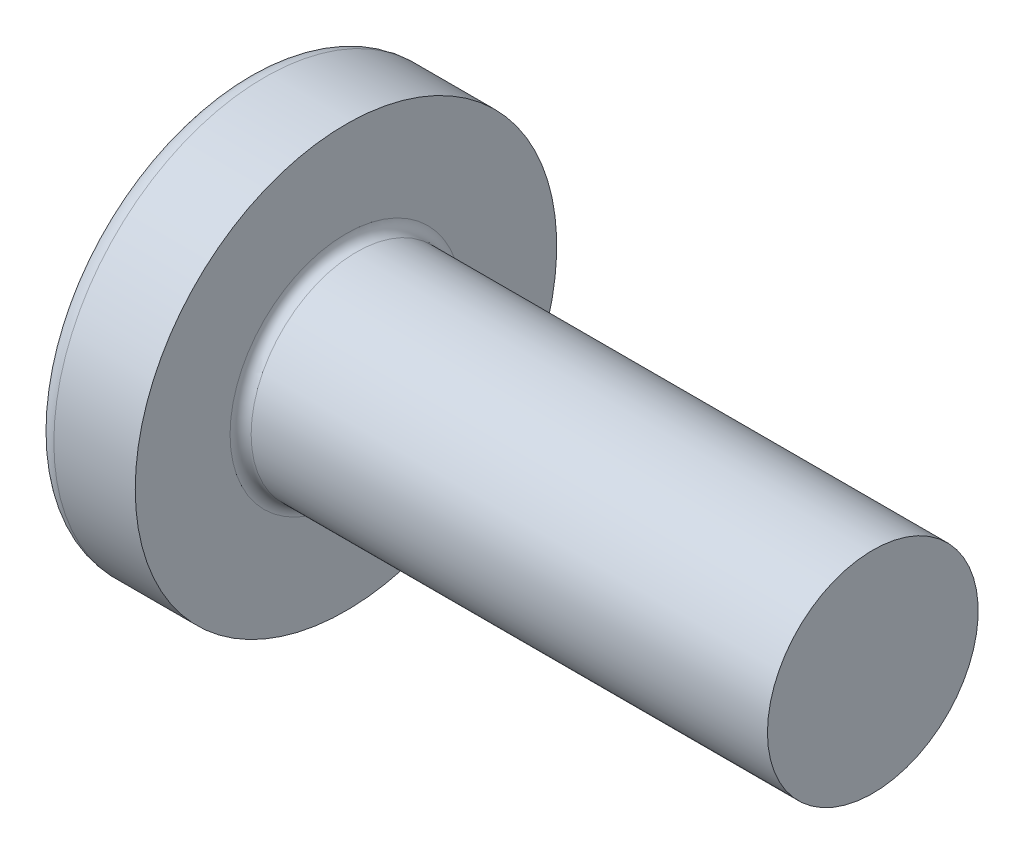
SolidWorks part; units mm, degrees
ref_plane "Plane1" through (0, 0, 0) normal (0, 0, 1) x (1, 0, 0)
ref_plane "Plane2" through (0, 0, 0) normal (0, 1, 0) x (1, 0, 0)
ref_plane "Plane3" through (0, 0, 0) normal (1, 0, 0) x (0, 0, -1)
sketch "BodySke" plane through (0, 0, 0) normal (0, 0, 1) x (1, 0, 0)
  line L0 (3.1, 2) -> (3.1, 4)
  line L1 (3.45, 6.35) -> (3.45, -3.175) construction
  line L2 (-25.4, 0) -> (127, 0) construction
  line L3 (13.1, 0) -> (0, 0)
  line L4 (3.1, 2) -> (13.1, 2)
  line L5 (13.1, 2) -> (13.1, 0)
  line L6 (1.5553, 4) -> (3.1, 4)
  line L8 (3.1, 6.35) -> (3.1, -3.175) construction
  arc A0 (1.2654, 3.8534) -> (0, 0) centre (6.5, 0) ccw
  arc A2 (1.2654, 3.8534) -> (1.5553, 4) centre (1.5553, 3.64) cw
  dimension "Head_fillet_rad" = 0.36
  dimension "Head_crown_rad" = 6.5
  dimension "Head_ht" = 3.1
  dimension "Diameter" = 4
  dimension "Length" = 10
  dimension "Head_dia" = 8
  dimension "Advance" = 0.7
  dimension "Thread_nom" = 10
revolve "Base-Revolve" add sketch "BodySke"
cosmetic thread "ThreadCosmetic" [suppressed]
fillet "Fillet1" radius 0.2
sketch "Sketch3" plane through (0, 0, 0) normal (1, 0, 0) x (0, 0, -1)
  line L0 (0.515, -2.15) -> (-0.515, -2.15)
  line L1 (0.515, -2.15) -> (0.515, 2.15)
  line L2 (-0.515, 2.15) -> (0.515, 2.15)
  line L3 (-0.515, 2.15) -> (-0.515, -2.15)
  dimension "D1" = 2.15
  dimension "Cross_dia" = 4.3
  dimension "D2" = 0.515
  dimension "Cross_width" = 1.03
ref_plane "Plane4" through (2.34, 0, 0) normal (1, 0, 0) x (0, 0, -1)
sketch "Sketch4" plane through (2.34, 0, 0) normal (1, 0, 0) x (0, 0, -1)
  line L0 (0.515, -0.9833) -> (-0.515, -0.9833)
  line L1 (0.515, -0.9833) -> (0.515, 0.9833)
  line L2 (-0.515, 0.9833) -> (0.515, 0.9833)
  line L3 (-0.515, 0.9833) -> (-0.515, -0.9833)
  dimension "D1" = 1.03
  dimension "D2" = 1.9666
  dimension "D3" = 0.515
  dimension "D4" = 0.9833
loft "Recess" cut profiles "Sketch3", "Sketch4"
pattern_circular "RecPat" count 2 every 90
sketch "RecCorSke" plane through (0, 0, 0) normal (0, 0, 1) x (1, 0, 0)
  line L0 (-3.175, 0) -> (15.875, 0) construction
  line L1 (-25.4, 0) -> (127, 0) construction
  line L2 (0, 0) -> (0, 1.0146)
  line L3 (0, 1.0146) -> (2.34, 0.851)
  line L4 (2.34, 0.851) -> (2.6165, 0)
  line L5 (2.6165, 0) -> (0, 0)
  dimension "Diameter" = 1.702
  dimension "Depth" = 2.34
  dimension "Draft_angle" = 4
  dimension "Bottom_angle" = 18
revolve "RecessCore" cut sketch "RecCorSke" angle 360 about L0
sketch "ThdSchSke" plane through (0, 0, 0) normal (0, 0, 1) x (1, 0, 0)
  line L0 (4.5, -1.61) -> (4.2269, -2)
  line L1 (4.5, -1.61) -> (4.7731, -2)
  line L2 (4.7731, -2) -> (4.7731, -2.5)
  line L3 (-3.175, 0) -> (5.1513, 0) construction
  line L5 (4.7731, -2.5) -> (4.2269, -2.5)
  line L6 (4.2269, -2.5) -> (4.2269, -2)
  dimension "Thread_minor" = 3.22
  dimension "Diameter" = 4
  dimension "Start" = 4.5
  dimension "SideAngle" = 55
  dimension "VeeAngle" = 70
  dimension "Overcut" = 5
revolve "ThreadSchematic" [suppressed] cut sketch "ThdSchSke" angle 360 about L3
pattern_linear "ThdSchPat" [suppressed]
equation "\"D1@Sketch3\" = \"Cross_dia@Sketch3\" / 2"
equation "\"D2@Sketch3\" = \"Cross_width@Sketch3\" / 2"
equation "\"Depth@RecCorSke\" = \"Cross_depth@Plane4\""
equation "\"D1@Sketch4\" = \"Cross_width@Sketch3\""
equation "\"D2@Sketch4\" = \"Cross_dia@Sketch3\" - 2.0 * \"Cross_depth@Plane4\" * tan(26.5  * 0.017453292)"
equation "\"D3@Sketch4\" = \"D1@Sketch4\" / 2"
equation "\"D4@Sketch4\" = \"D2@Sketch4\" / 2"
equation "\"Thread_length@ThreadCosmetic\" = ((sgn( (\"Length@BodySke\" - \"Advance@BodySke\" * 2.0 ) - \"Thread_nom@BodySke\" )-1)*( (\"Length@BodySke\" - \"Advance@BodySke\" * 2.0 ) - \"Thread_nom@BodySke\" ))/-2+ \"Thread_nom@BodySke\""
equation "\"Thread_minor@ThdSchSke\" = \"Thread_minor@ThreadCosmetic\""
equation "\"Diameter@ThdSchSke\" = \"Diameter@BodySke\""
equation "\"Overcut@ThdSchSke\" = \"Diameter@BodySke\" * 1.25"
equation "\"Start@ThdSchSke\" = \"Head_ht@BodySke\" + \"Length@BodySke\" - \"Thread_length@ThreadCosmetic\"  '---Non-countersunk---"
equation "\"Num_threads@ThdSchPat\" = int( \"Thread_length@ThreadCosmetic\" / \"Advance@BodySke\" + 0.999 )  + 1"
equation "\"Advance@ThdSchPat\" = \"Thread_length@ThreadCosmetic\" /  (\"Num_threads@ThdSchPat\" - 1) 'relax it"
